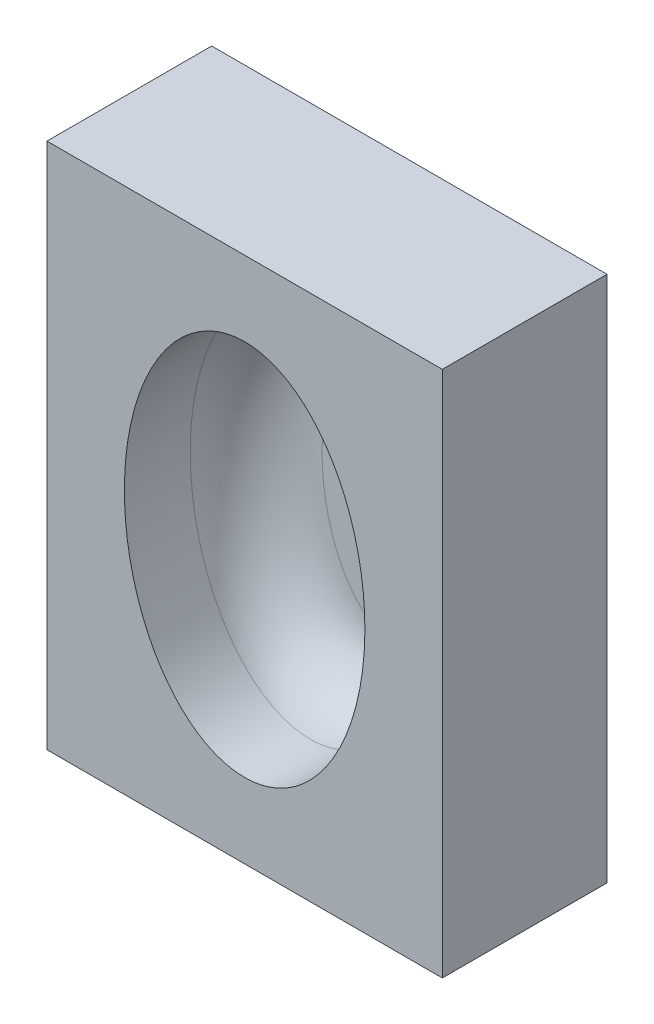
SolidWorks part; units mm, degrees
ref_plane "Alzado" through (0, 0, 0) normal (0, 0, 1) x (1, 0, 0)
ref_plane "Planta" through (0, 0, 0) normal (0, 1, 0) x (1, 0, 0)
ref_plane "Vista lateral" through (0, 0, 0) normal (1, 0, 0) x (0, 0, -1)
sketch "Croquis1" plane through (0, 0, 0) normal (0, 1, 0) x (1, 0, 0)
  line L0 (0, 0) -> (-30, 0)
  line L1 (-30, 0) -> (-30, 25)
  line L2 (-30, 25) -> (30, 25)
  line L3 (30, 25) -> (30, 0)
  line L4 (30, 0) -> (0, 0)
extrude "Saliente-Extruir1" add sketch "Croquis1" along normal blind 80
sketch "Croquis2" plane through (0, 0, 0) normal (0, 0, 1) x (1, 0, 0)
  line L0 (0, 0) -> (0, 40)
  ellipse E0 centre (0, 40) end of major axis (0, 68.6419) minor radius 18.2522
  point P3 (0, 68.6419)
extrude "Cortar-Extruir1" cut sketch "Croquis2" against normal blind 20
fillet "Redondeo1" radius 10 1 edges at (0, 68.6419, -20)
